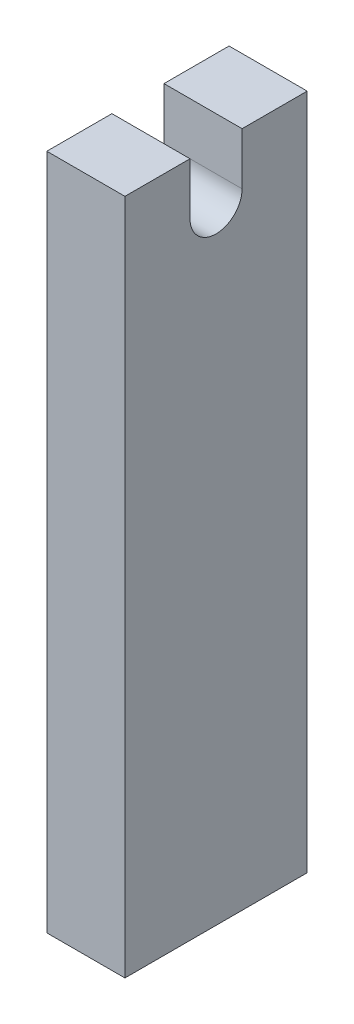
SolidWorks part; units mm, degrees
material "Pine"
ref_plane "Front Plane" through (0, 0, 0) normal (0, 0, 1) x (1, 0, 0)
ref_plane "Top Plane" through (0, 0, 0) normal (0, 1, 0) x (1, 0, 0)
ref_plane "Right Plane" through (0, 0, 0) normal (1, 0, 0) x (0, 0, -1)
sketch "Sketch1" plane through (0, 0, 0) normal (0, 1, 0) x (1, 0, 0)
  line L1 (0, 0) -> (38.1, 0)
  line L2 (0, 0) -> (0, 88.9)
  line L3 (0, 88.9) -> (38.1, 88.9)
  line L4 (38.1, 0) -> (38.1, 88.9)
  dimension "D1" = 38.1
  dimension "D2" = 88.9
extrude "Boss-Extrude1" add sketch "Sketch1" along normal blind 330.2
sketch "Sketch2" plane through (38.1, 0, 0) normal (1, 0, 0) x (0, 0, -1)
  line L0 (44.45, 330.2) -> (44.45, 304.8) construction
  line L1 (0, 330.2) -> (88.9, 330.2) construction
  line L2 (57.15, 330.2) -> (57.15, 304.8)
  line L3 (31.75, 330.2) -> (31.75, 304.8)
  arc A0 (57.15, 330.2) -> (31.75, 330.2) centre (44.45, 330.2) ccw
  arc A1 (31.75, 304.8) -> (57.15, 304.8) centre (44.45, 304.8) ccw
  point P4 (44.45, 317.5)
  dimension "D1" = 12.7
  dimension "D2" = 25.4
extrude "Cut-Extrude1" cut sketch "Sketch2" against normal blind 381
